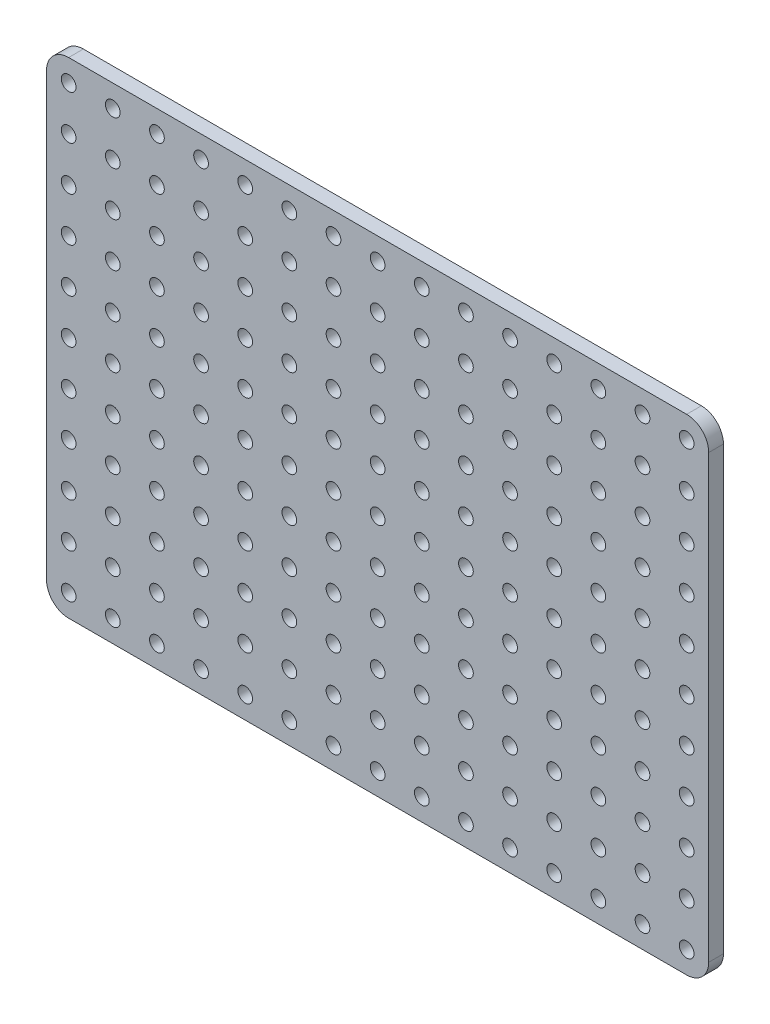
SolidWorks part; units mm, degrees
ref_plane "Alzado" through (0, 0, 0) normal (0, 0, 1) x (1, 0, 0)
ref_plane "Planta" through (0, 0, 0) normal (0, 1, 0) x (1, 0, 0)
ref_plane "Vista lateral" through (0, 0, 0) normal (1, 0, 0) x (0, 0, -1)
sketch "Model" plane through (0, 0, 0) normal (0, 0, 1) x (1, 0, 0)
  line L0 (391.4291, 489.7422) -> (517.4291, 489.7422)
  line L1 (521.9291, 485.2422) -> (521.9291, 395.2422)
  line L2 (391.4291, 390.7422) -> (517.4291, 390.7422)
  line L3 (386.9291, 485.2422) -> (386.9291, 395.2422)
  arc A0 (521.9291, 485.2422) -> (517.4291, 489.7422) centre (517.4291, 485.2422) ccw
  circle A1 centre (391.4291, 485.2422) radius 1.5
  circle A2 centre (391.4291, 476.2422) radius 1.5
  circle A3 centre (391.4291, 467.2422) radius 1.5
  circle A4 centre (391.4291, 458.2422) radius 1.5
  circle A5 centre (391.4291, 449.2422) radius 1.5
  circle A6 centre (391.4291, 440.2422) radius 1.5
  circle A7 centre (391.4291, 431.2422) radius 1.5
  circle A8 centre (391.4291, 422.2422) radius 1.5
  circle A9 centre (391.4291, 413.2422) radius 1.5
  circle A10 centre (391.4291, 404.2422) radius 1.5
  circle A11 centre (391.4291, 395.2422) radius 1.5
  circle A12 centre (400.4291, 485.2422) radius 1.5
  circle A13 centre (400.4291, 476.2422) radius 1.5
  circle A14 centre (400.4291, 467.2422) radius 1.5
  circle A15 centre (400.4291, 458.2422) radius 1.5
  circle A16 centre (400.4291, 449.2422) radius 1.5
  circle A17 centre (400.4291, 440.2422) radius 1.5
  circle A18 centre (400.4291, 431.2422) radius 1.5
  circle A19 centre (400.4291, 422.2422) radius 1.5
  circle A20 centre (400.4291, 413.2422) radius 1.5
  circle A21 centre (400.4291, 404.2422) radius 1.5
  circle A22 centre (400.4291, 395.2422) radius 1.5
  circle A23 centre (409.4291, 485.2422) radius 1.5
  circle A24 centre (409.4291, 476.2422) radius 1.5
  circle A25 centre (409.4291, 467.2422) radius 1.5
  circle A26 centre (409.4291, 458.2422) radius 1.5
  circle A27 centre (409.4291, 449.2422) radius 1.5
  circle A28 centre (409.4291, 440.2422) radius 1.5
  circle A29 centre (409.4291, 431.2422) radius 1.5
  circle A30 centre (409.4291, 422.2422) radius 1.5
  circle A31 centre (409.4291, 413.2422) radius 1.5
  circle A32 centre (409.4291, 404.2422) radius 1.5
  circle A33 centre (409.4291, 395.2422) radius 1.5
  circle A34 centre (418.4291, 485.2422) radius 1.5
  circle A35 centre (418.4291, 476.2422) radius 1.5
  circle A36 centre (418.4291, 467.2422) radius 1.5
  circle A37 centre (418.4291, 458.2422) radius 1.5
  circle A38 centre (418.4291, 449.2422) radius 1.5
  circle A39 centre (418.4291, 440.2422) radius 1.5
  circle A40 centre (418.4291, 431.2422) radius 1.5
  circle A41 centre (418.4291, 422.2422) radius 1.5
  circle A42 centre (418.4291, 413.2422) radius 1.5
  circle A43 centre (418.4291, 404.2422) radius 1.5
  circle A44 centre (418.4291, 395.2422) radius 1.5
  circle A45 centre (427.4291, 485.2422) radius 1.5
  circle A46 centre (427.4291, 476.2422) radius 1.5
  circle A47 centre (427.4291, 467.2422) radius 1.5
  circle A48 centre (427.4291, 458.2422) radius 1.5
  circle A49 centre (427.4291, 449.2422) radius 1.5
  circle A50 centre (427.4291, 440.2422) radius 1.5
  circle A51 centre (427.4291, 431.2422) radius 1.5
  circle A52 centre (427.4291, 422.2422) radius 1.5
  circle A53 centre (427.4291, 413.2422) radius 1.5
  circle A54 centre (427.4291, 404.2422) radius 1.5
  circle A55 centre (427.4291, 395.2422) radius 1.5
  circle A56 centre (436.4291, 485.2422) radius 1.5
  circle A57 centre (436.4291, 476.2422) radius 1.5
  circle A58 centre (436.4291, 467.2422) radius 1.5
  circle A59 centre (436.4291, 458.2422) radius 1.5
  circle A60 centre (436.4291, 449.2422) radius 1.5
  circle A61 centre (436.4291, 440.2422) radius 1.5
  circle A62 centre (436.4291, 431.2422) radius 1.5
  circle A63 centre (436.4291, 422.2422) radius 1.5
  circle A64 centre (436.4291, 413.2422) radius 1.5
  circle A65 centre (436.4291, 404.2422) radius 1.5
  circle A66 centre (436.4291, 395.2422) radius 1.5
  circle A67 centre (445.4291, 485.2422) radius 1.5
  circle A68 centre (445.4291, 476.2422) radius 1.5
  circle A69 centre (445.4291, 467.2422) radius 1.5
  circle A70 centre (445.4291, 458.2422) radius 1.5
  circle A71 centre (445.4291, 449.2422) radius 1.5
  circle A72 centre (445.4291, 440.2422) radius 1.5
  circle A73 centre (445.4291, 431.2422) radius 1.5
  circle A74 centre (445.4291, 422.2422) radius 1.5
  circle A75 centre (445.4291, 413.2422) radius 1.5
  circle A76 centre (445.4291, 404.2422) radius 1.5
  circle A77 centre (445.4291, 395.2422) radius 1.5
  circle A78 centre (454.4291, 485.2422) radius 1.5
  circle A79 centre (454.4291, 476.2422) radius 1.5
  circle A80 centre (454.4291, 467.2422) radius 1.5
  circle A81 centre (454.4291, 458.2422) radius 1.5
  circle A82 centre (454.4291, 449.2422) radius 1.5
  circle A83 centre (454.4291, 440.2422) radius 1.5
  circle A84 centre (454.4291, 431.2422) radius 1.5
  circle A85 centre (454.4291, 422.2422) radius 1.5
  circle A86 centre (454.4291, 413.2422) radius 1.5
  circle A87 centre (454.4291, 404.2422) radius 1.5
  circle A88 centre (454.4291, 395.2422) radius 1.5
  circle A89 centre (463.4291, 485.2422) radius 1.5
  circle A90 centre (463.4291, 476.2422) radius 1.5
  circle A91 centre (463.4291, 467.2422) radius 1.5
  circle A92 centre (463.4291, 458.2422) radius 1.5
  circle A93 centre (463.4291, 449.2422) radius 1.5
  circle A94 centre (463.4291, 440.2422) radius 1.5
  circle A95 centre (463.4291, 431.2422) radius 1.5
  circle A96 centre (463.4291, 422.2422) radius 1.5
  circle A97 centre (463.4291, 413.2422) radius 1.5
  circle A98 centre (463.4291, 404.2422) radius 1.5
  circle A99 centre (463.4291, 395.2422) radius 1.5
  circle A100 centre (472.4291, 485.2422) radius 1.5
  circle A101 centre (472.4291, 476.2422) radius 1.5
  circle A102 centre (472.4291, 467.2422) radius 1.5
  circle A103 centre (472.4291, 458.2422) radius 1.5
  circle A104 centre (472.4291, 449.2422) radius 1.5
  circle A105 centre (472.4291, 440.2422) radius 1.5
  circle A106 centre (472.4291, 431.2422) radius 1.5
  circle A107 centre (472.4291, 422.2422) radius 1.5
  circle A108 centre (472.4291, 413.2422) radius 1.5
  circle A109 centre (472.4291, 404.2422) radius 1.5
  circle A110 centre (472.4291, 395.2422) radius 1.5
  circle A111 centre (481.4291, 485.2422) radius 1.5
  circle A112 centre (481.4291, 476.2422) radius 1.5
  circle A113 centre (481.4291, 467.2422) radius 1.5
  circle A114 centre (481.4291, 458.2422) radius 1.5
  circle A115 centre (481.4291, 449.2422) radius 1.5
  circle A116 centre (481.4291, 440.2422) radius 1.5
  circle A117 centre (481.4291, 431.2422) radius 1.5
  circle A118 centre (481.4291, 422.2422) radius 1.5
  circle A119 centre (481.4291, 413.2422) radius 1.5
  circle A120 centre (481.4291, 404.2422) radius 1.5
  circle A121 centre (481.4291, 395.2422) radius 1.5
  circle A122 centre (490.4291, 485.2422) radius 1.5
  circle A123 centre (490.4291, 476.2422) radius 1.5
  circle A124 centre (490.4291, 467.2422) radius 1.5
  circle A125 centre (490.4291, 458.2422) radius 1.5
  circle A126 centre (490.4291, 449.2422) radius 1.5
  circle A127 centre (490.4291, 440.2422) radius 1.5
  circle A128 centre (490.4291, 431.2422) radius 1.5
  circle A129 centre (490.4291, 422.2422) radius 1.5
  circle A130 centre (490.4291, 413.2422) radius 1.5
  circle A131 centre (490.4291, 404.2422) radius 1.5
  circle A132 centre (490.4291, 395.2422) radius 1.5
  circle A133 centre (499.4291, 485.2422) radius 1.5
  circle A134 centre (499.4291, 476.2422) radius 1.5
  circle A135 centre (499.4291, 467.2422) radius 1.5
  circle A136 centre (499.4291, 458.2422) radius 1.5
  circle A137 centre (499.4291, 449.2422) radius 1.5
  circle A138 centre (499.4291, 440.2422) radius 1.5
  circle A139 centre (499.4291, 431.2422) radius 1.5
  circle A140 centre (499.4291, 422.2422) radius 1.5
  circle A141 centre (499.4291, 413.2422) radius 1.5
  circle A142 centre (499.4291, 404.2422) radius 1.5
  circle A143 centre (499.4291, 395.2422) radius 1.5
  circle A144 centre (508.4291, 485.2422) radius 1.5
  circle A145 centre (508.4291, 476.2422) radius 1.5
  circle A146 centre (508.4291, 467.2422) radius 1.5
  circle A147 centre (508.4291, 458.2422) radius 1.5
  circle A148 centre (508.4291, 449.2422) radius 1.5
  circle A149 centre (508.4291, 440.2422) radius 1.5
  circle A150 centre (508.4291, 431.2422) radius 1.5
  circle A151 centre (508.4291, 422.2422) radius 1.5
  circle A152 centre (508.4291, 413.2422) radius 1.5
  circle A153 centre (508.4291, 404.2422) radius 1.5
  circle A154 centre (508.4291, 395.2422) radius 1.5
  circle A155 centre (517.4291, 485.2422) radius 1.5
  circle A156 centre (517.4291, 476.2422) radius 1.5
  circle A157 centre (517.4291, 467.2422) radius 1.5
  circle A158 centre (517.4291, 458.2422) radius 1.5
  circle A159 centre (517.4291, 449.2422) radius 1.5
  circle A160 centre (517.4291, 440.2422) radius 1.5
  circle A161 centre (517.4291, 431.2422) radius 1.5
  circle A162 centre (517.4291, 422.2422) radius 1.5
  circle A163 centre (517.4291, 413.2422) radius 1.5
  circle A164 centre (517.4291, 404.2422) radius 1.5
  circle A165 centre (517.4291, 395.2422) radius 1.5
  arc A166 (391.4291, 489.7422) -> (386.9291, 485.2422) centre (391.4291, 485.2422) ccw
  arc A167 (386.9291, 395.2422) -> (391.4291, 390.7422) centre (391.4291, 395.2422) ccw
  arc A168 (517.4291, 390.7422) -> (521.9291, 395.2422) centre (517.4291, 395.2422) ccw
extrude "Saliente-Extruir1" add sketch "Model" along normal blind 3
